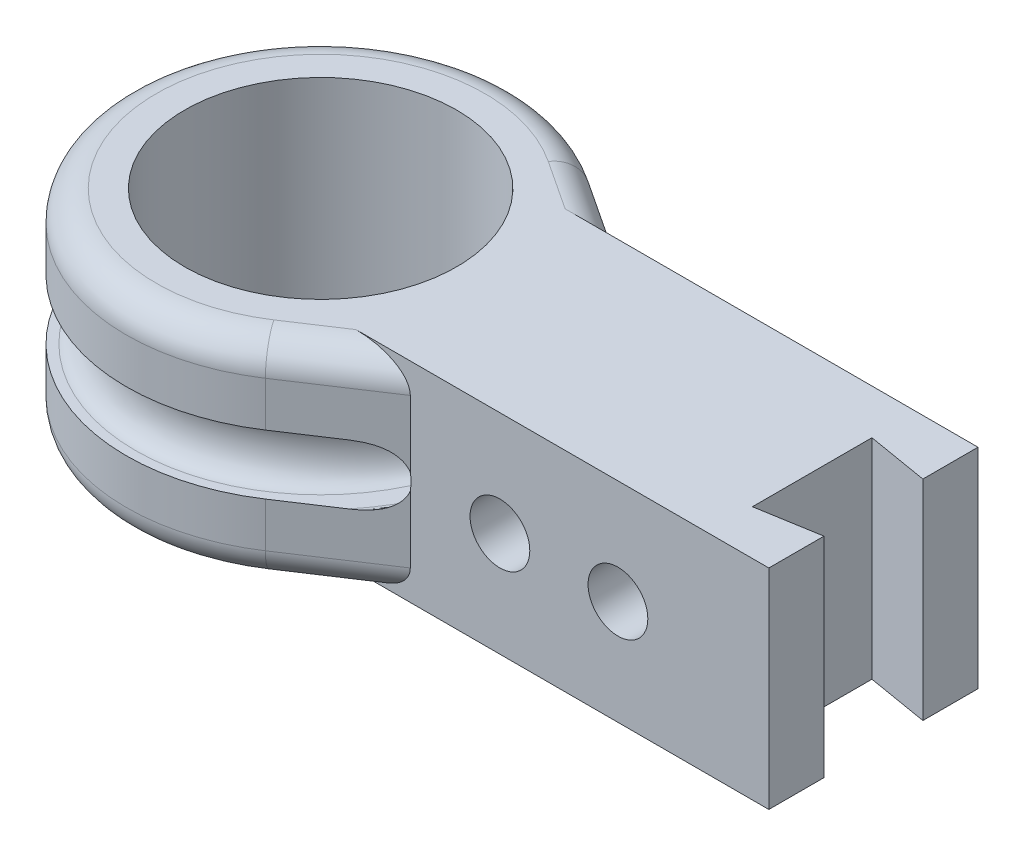
SolidWorks part; units mm, degrees
ref_plane "Front Plane" through (0, 0, 0) normal (0, 0, 1) x (1, 0, 0)
ref_plane "Top Plane" through (0, 0, 0) normal (0, 1, 0) x (1, 0, 0)
ref_plane "Right Plane" through (0, 0, 0) normal (1, 0, 0) x (0, 0, -1)
sketch "Sketch1" plane through (0, 0, 0) normal (0, 1, 0) x (1, 0, 0)
  line L0 (-10.3258, 0) -> (22.3498, 0) construction
  line L1 (6.5, 3.5) -> (3.578, 5.4266)
  line L2 (6.5, -3.5) -> (18.5, -3.5)
  line L4 (6.5, 3.5) -> (18.5, 3.5)
  line L5 (18.5, -3.5) -> (18.5, -1.655)
  line L6 (6.5, -3.5) -> (18.5, 3.5) construction
  line L7 (6.5, 3.5) -> (18.5, -3.5) construction
  line L8 (6.5, -3.5) -> (3.578, -5.4266)
  line L9 (18.5, 1.655) -> (16.45, 2)
  line L13 (16.45, -2) -> (16.45, 2)
  line L16 (16.45, -2) -> (18.5, -1.655)
  line L17 (18.5, 1.655) -> (18.5, 3.5)
  arc A0 (3.578, 5.4266) -> (3.578, -5.4266) centre (0, 0) ccw
  circle A1 centre (0, 0) radius 4.55
  point P4 (16.45, 0)
  point P5 (12.5, 0)
  point P11 (18.5, 0)
  point P18 (18.5, 1.655)
  point P19 (18.5, 2.255)
  point P23 (18.5, -1.655)
  dimension "D1" = 13
  dimension "D2" = 9.1
  dimension "D3" = 12
  dimension "D4" = 7
  dimension "D5" = 4
  dimension "D6" = 1.845
  dimension "D7" = 0.6
extrude "Boss-Extrude2" add sketch "Sketch1" along normal blind 7 contours A1 | L2 L5 L16 L13 L9 L17 L4 L1 A0 L8
sketch "Sketch2" plane through (0, 0, 0) normal (1, 0, 0) x (0, -1, 0)
  line L0 (0, -0.6001) -> (0, 7.5244) construction
  line L1 (-4.5, 6.805) -> (-4.5, 6.195)
  line L2 (-2.5, 6.195) -> (-2.5, 6.805)
  line L3 (-7.3353, 0) -> (0.2116, 0) construction
  line L4 (-7.3353, 6.5) -> (0.2116, 6.5) construction
  ellipse E0 centre (-3.5, 6.195) end of major axis (-4.5, 6.195) minor radius 0.6 (-4.5, 6.195) -> (-2.5, 6.195) ccw
  ellipse E1 centre (-3.5, 6.805) end of major axis (-4.5, 6.805) minor radius 0.6 (-4.5, 6.805) -> (-2.5, 6.805) cw
  point P5 (-4.5, 6.5)
  point P6 (-2.5, 6.5)
  point P20 (0, 6.5)
  dimension "D1" = 0.61
  dimension "D2" = 2
  dimension "D3" = 2.5
revolve "Cut-Revolve1" cut sketch "Sketch2" angle 360 about L3
sketch "Sketch3" plane through (0, 0, 3.5) normal (0, 0, 1) x (1, 0, 0)
  line L0 (18.5, 3.5) -> (6.0558, 3.5) construction
  line L1 (18.5, 7) -> (18.5, 0) construction
  line L2 (16.45, 7.1416) -> (16.45, -0.1293) construction
  circle A2 centre (13.45, 3.5) radius 1
  circle A3 centre (9.5, 3.5) radius 1
  point P4 (14.45, 3.5)
  point P5 (13.45, 3.5)
  point P11 (9.5, 3.5)
  point P13 (16.45, 3.5)
  dimension "D1" = 2
  dimension "D3" = 3.95
  dimension "D2" = 3
  dimension "D4" = 2.05
extrude "Cut-Extrude1" cut sketch "Sketch3" against normal up to next contours A3 | A2
fillet "Fillet4" radius 1 6 edges at (5.039, 0, -4.4633) (5.039, 0, 4.4633) (5.039, 7, -4.4633) (5.039, 7, 4.4633) (-6.5, 0, 0) (-6.5, 7, 0)
